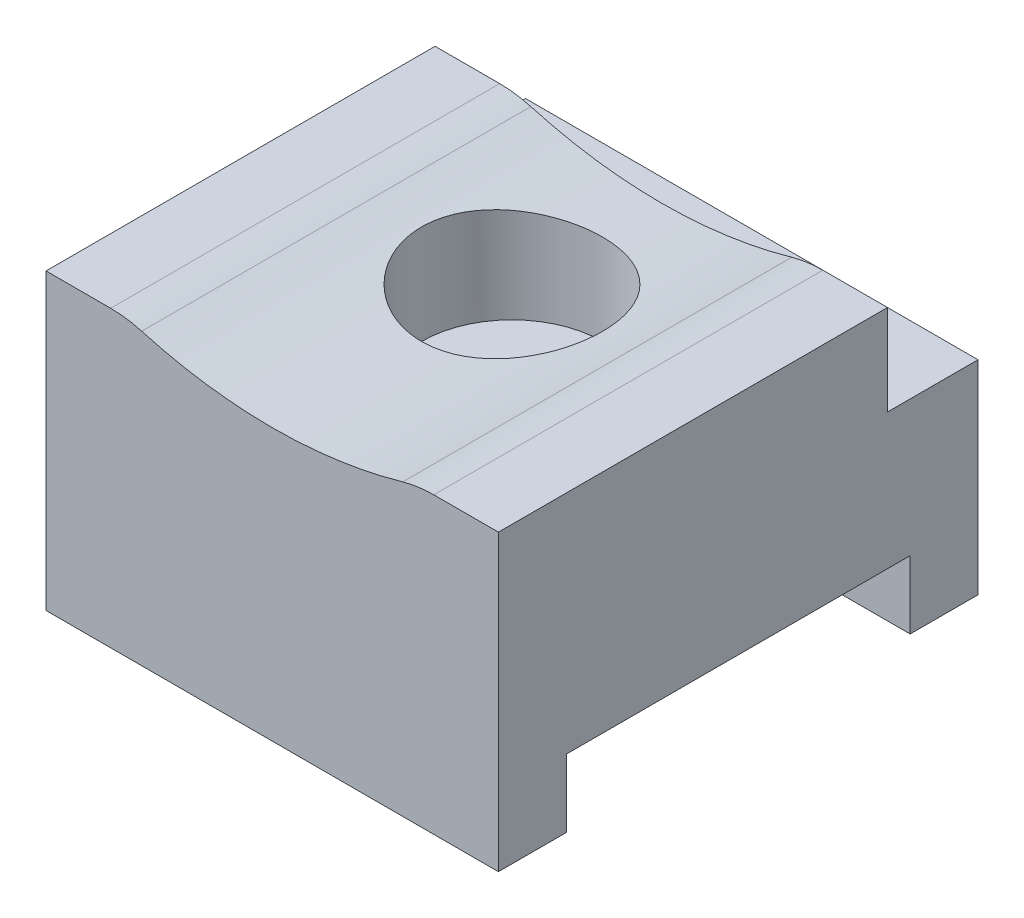
SolidWorks part; units mm, degrees
material "PLA"
ref_plane "前视基准面" through (0, 0, 0) normal (0, 0, 1) x (1, 0, 0)
ref_plane "上视基准面" through (0, 0, 0) normal (0, 1, 0) x (1, 0, 0)
ref_plane "右视基准面" through (0, 0, 0) normal (1, 0, 0) x (0, 0, -1)
sketch "草图1" plane through (0, 0, 0) normal (1, 0, 0) x (0, 0, -1)
  line L0 (0, 0) -> (0, 10) construction
  line L1 (-10.6, 10) -> (10.6, 10)
  line L2 (10.6, 10) -> (10.6, -3)
  line L3 (10.6, -3) -> (7.6, -3)
  line L4 (7.6, -3) -> (7.6, 0)
  line L5 (7.6, 0) -> (-7.6, 0)
  line L6 (-7.6, -3) -> (-7.6, 0)
  line L7 (-10.6, -3) -> (-7.6, -3)
  line L8 (-10.6, 10) -> (-10.6, -3)
  dimension "D1" = 3
  dimension "D2" = 15.2
  dimension "D3" = 10
  dimension "D4" = 3
extrude "凸台-拉伸1" add sketch "草图1" along normal blind 20
sketch "草图2" plane through (0, 0, 10.6) normal (0, 0, 1) x (1, 0, 0)
  line L0 (20, 10) -> (0, 10) construction
  circle A0 centre (10, 30) radius 21
  point P6 (10, 10)
  dimension "D1" = 42
  dimension "D2" = 30
extrude "切除-拉伸1" cut sketch "草图2" against normal through all
sketch "草图3" plane through (0, 0, 0) normal (0, -1, 0) x (1, 0, 0)
  line L0 (20, 7.6) -> (0, 7.6) construction
  circle A0 centre (10, 0) radius 1.6
  point P7 (10, 7.6)
  dimension "D1" = 3.2
extrude "切除-拉伸2" cut sketch "草图3" against normal through all
ref_plane "基准面1" through (0, 5, 0) normal (0, -1, 0) x (-1, 0, 0)
sketch "草图4" plane through (0, 5, 0) normal (0, -1, 0) x (-1, 0, 0)
  circle A0 centre (-10, 0) radius 4
  dimension "D1" = 8
extrude "切除-拉伸3" cut sketch "草图4" against normal through all
fillet "圆角1" radius 5 2 edges at (3.5969, 10, 0) (16.4031, 10, 0)
sketch "草图5" plane through (20, 0, 0) normal (1, 0, 0) x (0, 0, -1)
  line L1 (10.6, 10) -> (6.6, 10)
  line L2 (10.6, 10) -> (10.6, 6)
  line L3 (10.6, 6) -> (6.6, 6)
  line L4 (6.6, 10) -> (6.6, 6)
  dimension "D1" = 4
  dimension "D2" = 4
extrude "切除-拉伸4" cut sketch "草图5" against normal through all
sketch "草图6" plane through (0, 0, 0) normal (0, -1, 0) x (1, 0, 0)
  circle A0 centre (10, 0) radius 4
  dimension "D1" = 8
extrude "切除-拉伸5" cut sketch "草图6" against normal blind 1
